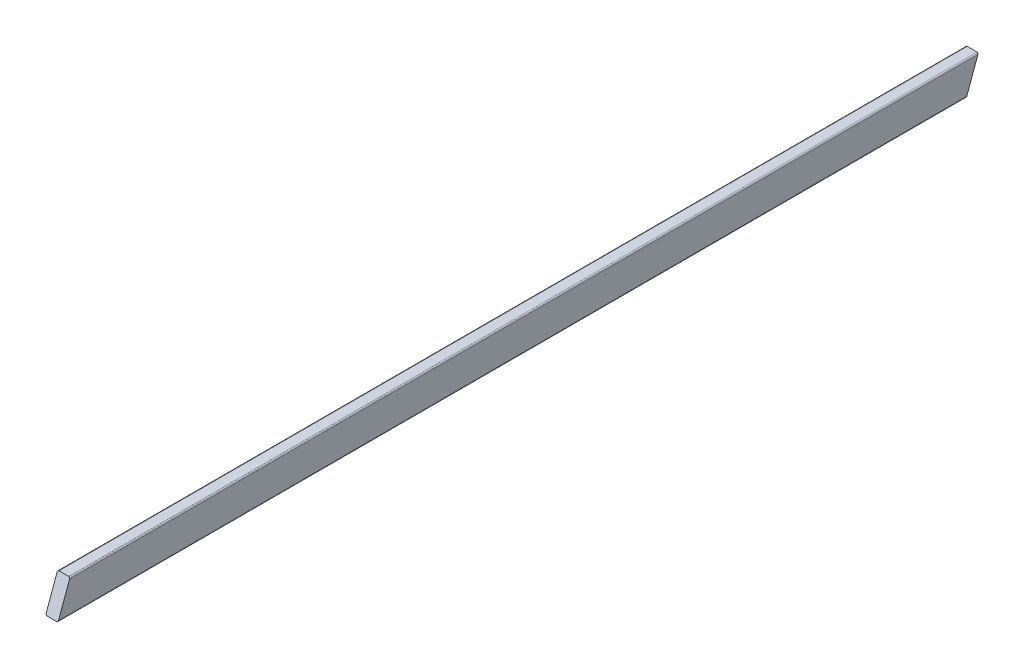
SolidWorks part; units mm, degrees
ref_plane "Front Plane" through (0, 0, 0) normal (0, 0, 1) x (1, 0, 0)
ref_plane "Top Plane" through (0, 0, 0) normal (0, 1, 0) x (1, 0, 0)
ref_plane "Right Plane" through (0, 0, 0) normal (1, 0, 0) x (0, 0, -1)
sketch "Esboço1" plane through (0, 0, 0) normal (0, 0, 1) x (1, 0, 0)
  line L1 (-4.7625, -12.7) -> (4.7625, -12.7)
  line L2 (-4.7625, -12.7) -> (-4.7625, 12.7)
  line L3 (-4.7625, 12.7) -> (4.7625, 12.7)
  line L4 (4.7625, -12.7) -> (4.7625, 12.7)
  line L5 (-4.7625, -12.7) -> (4.7625, 12.7) construction
  line L6 (-4.7625, 12.7) -> (4.7625, -12.7) construction
  point P0 (0, 0)
  dimension "D1" = 9.525
  dimension "D2" = 25.4
extrude "Ressalto-extrusão1" add sketch "Esboço1" along normal mid plane 800
sketch "Esboço3" plane through (4.7625, 0, 0) normal (1, 0, 0) x (0, 0, -1)
  line L0 (-353.1566, -12.7) -> (343.9118, -12.7)
  line L1 (-353.1566, -12.7) -> (-343.9118, 12.7)
  line L2 (343.9118, -12.7) -> (353.1566, 12.7)
  line L3 (-343.9118, 12.7) -> (353.1566, 12.7)
  line L4 (-400, 12.7) -> (400, 12.7) construction
  line L5 (-400, -12.7) -> (400, -12.7) construction
  line L6 (-348.5342, 0) -> (348.5342, 0) construction
  line L7 (-400, -12.7) -> (-400, 12.7) construction
  point P10 (0, 0)
  dimension "D1" = 20
  dimension "D2" = 655.03
extrude "Corte-extrusão2" cut sketch "Esboço3" against normal through all flip side to cut
fillet "Filete1" radius 1 4 edges at (-4.7625, -12.7, 4.6224) (4.7625, -12.7, 4.6224) (-4.7625, 12.7, -4.6224) (4.7625, 12.7, -4.6224)
